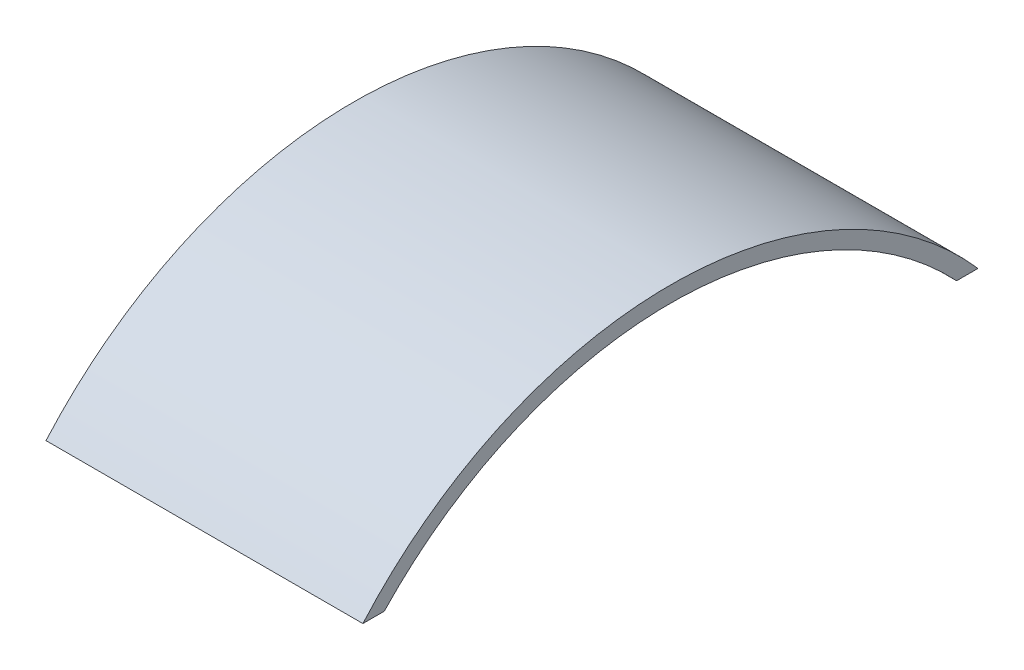
SolidWorks part; units mm, degrees
ref_plane "Front Plane" through (0, 0, 0) normal (0, 0, 1) x (1, 0, 0)
ref_plane "Top Plane" through (0, 0, 0) normal (0, 1, 0) x (1, 0, 0)
ref_plane "Right Plane" through (0, 0, 0) normal (1, 0, 0) x (0, 0, -1)
sketch "Sketch1" plane through (0, 0, 0) normal (1, 0, 0) x (0, 0, -1)
  line L2 (-1.806, 1.7) -> (-1.9411, 1.7)
  line L3 (1.806, 1.7) -> (1.9411, 1.7)
  line L5 (-2.0243, 1.6) -> (2.0243, 1.6) construction
  line L6 (-1.806, 1.7) -> (1.806, 1.7) construction
  arc A0 (1.806, 1.7) -> (-1.806, 1.7) centre (0, 0) ccw
  arc A1 (1.9411, 1.7) -> (-1.9411, 1.7) centre (0, 0) ccw
  arc A2 (2.0243, 1.6) -> (-2.0243, 1.6) centre (0, 0) ccw construction
  dimension "D1" = 0.1
extrude "Boss-Extrude1" add sketch "Sketch1" along normal blind 2
